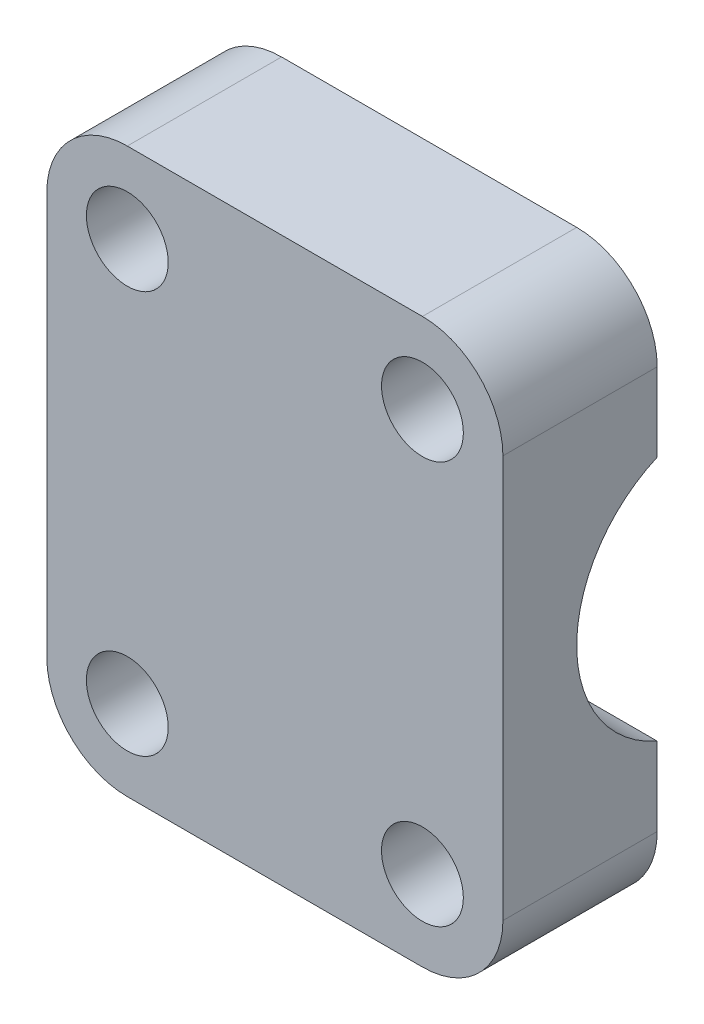
SolidWorks part; units mm, degrees
ref_plane "前视基准面" through (0, 0, 0) normal (0, 0, 1) x (1, 0, 0)
ref_plane "上视基准面" through (0, 0, 0) normal (0, 1, 0) x (1, 0, 0)
ref_plane "右视基准面" through (0, 0, 0) normal (1, 0, 0) x (0, 0, -1)
sketch "草图1" plane through (0, 0, 0) normal (0, 0, 1) x (1, 0, 0)
  line L1 (5.5, -7.5) -> (-5.5, -7.5) construction
  line L2 (5.5, -7.5) -> (5.5, 7.5) construction
  line L3 (5.5, 7.5) -> (-5.5, 7.5) construction
  line L4 (-5.5, -7.5) -> (-5.5, 7.5) construction
  line L5 (5.5, -7.5) -> (-5.5, 7.5) construction
  line L6 (5.5, 7.5) -> (-5.5, -7.5) construction
  line L7 (8.5, -10.5) -> (-8.5, -10.5)
  line L8 (8.5, -10.5) -> (8.5, 10.5)
  line L9 (8.5, 10.5) -> (-8.5, 10.5)
  line L10 (-8.5, -10.5) -> (-8.5, 10.5)
  line L11 (8.5, -10.5) -> (-8.5, 10.5) construction
  line L12 (8.5, 10.5) -> (-8.5, -10.5) construction
  circle A0 centre (-5.5, 7.5) radius 1.525
  circle A1 centre (5.5, 7.5) radius 1.525
  circle A2 centre (5.5, -7.5) radius 1.525
  circle A3 centre (-5.5, -7.5) radius 1.525
  point P0 (0, 0)
  point P10 (0, 0)
  dimension "D3" = 3.05
  dimension "D5" = 3
  dimension "D1" = 11
  dimension "D2" = 15
  dimension "D4" = 3
extrude "凸台-拉伸1" add sketch "草图1" along normal blind 5.75 from offset 2
sketch "草图2" plane through (8.5, 0, 0) normal (1, 0, 0) x (0, 0, -1)
  circle A0 centre (0, 0) radius 5
  dimension "D1" = 10
extrude "切除-拉伸2" cut sketch "草图2" against normal through all contours A0
fillet "圆角1" radius 3 4 edges at (-8.5, -10.5, 4.875) (-8.5, 10.5, 4.875) (8.5, -10.5, 4.875) (8.5, 10.5, 4.875)
